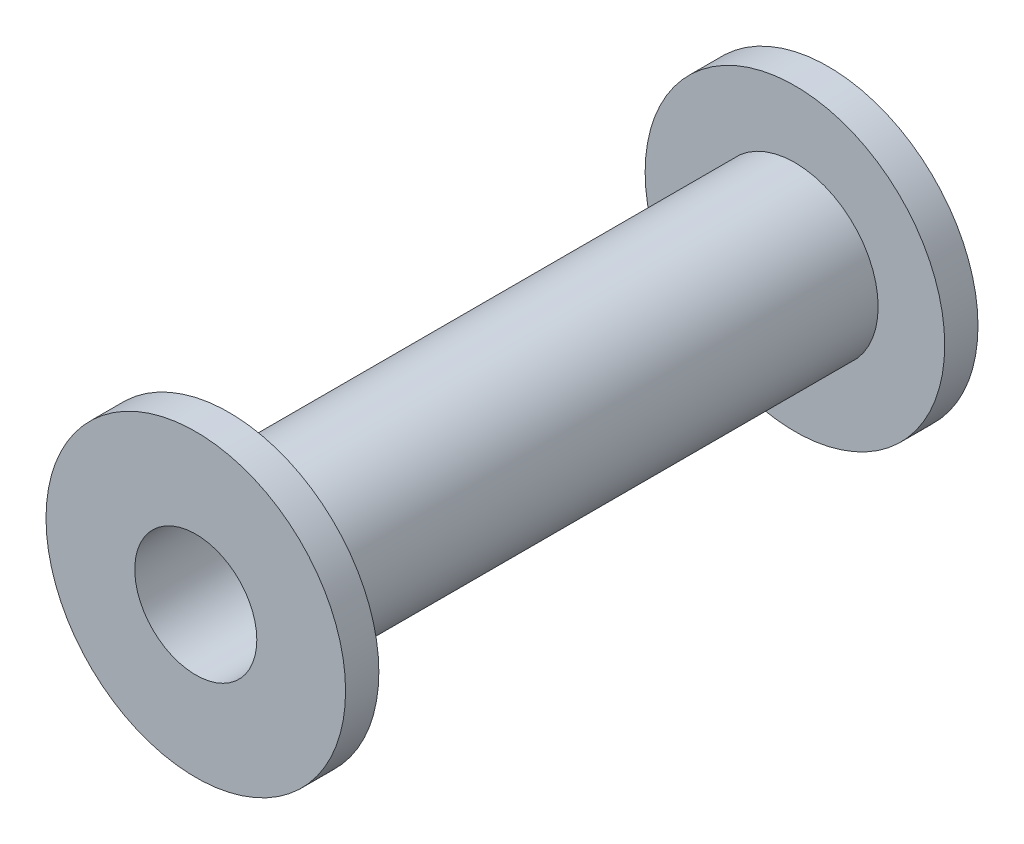
SolidWorks part; units mm, degrees
other "Marcação1"
sketch "Esboço7" plane through (13.5, -13.5, 0) normal (0.9554, -0.1863, -0.2291) x (-0.2848, -0.3761, -0.8818)
material "Filme de alta densidade PE"
ref_plane "Plano frontal" through (0, 0, 0) normal (0, 0, 1) x (1, 0, 0)
ref_plane "Plano superior" through (0, 0, 0) normal (0, 1, 0) x (1, 0, 0)
ref_plane "Plano direito" through (0, 0, 0) normal (1, 0, 0) x (0, 0, -1)
sketch "Esboço1" plane through (0, 0, 0) normal (0, 0, 1) x (1, 0, 0)
  circle A0 centre (0, 0) radius 5.5
  circle A1 centre (0, 0) radius 13.5
  dimension "D1" = 11
  dimension "D2" = 27
extrude "Ressalto-extrusão1" add sketch "Esboço1" along normal blind 3
sketch "Esboço2" plane through (0, 0, 3) normal (0, 0, 1) x (1, 0, 0)
  circle A0 centre (0, 0) radius 7.5
  circle A1 centre (0, 0) radius 5.5
  circle A2 centre (0, 0) radius 5.5 construction
  dimension "D1" = 15
extrude "Ressalto-extrusão2" add sketch "Esboço2" along normal blind 51
sketch "Esboço3" plane through (0, 0, 54) normal (0, 0, 1) x (1, 0, 0)
  circle A0 centre (0, 0) radius 13.5
  circle A1 centre (0, 0) radius 5.5
  dimension "D1" = 11
  dimension "D2" = 27
extrude "Ressalto-extrusão3" add sketch "Esboço3" along normal blind 3
sketch "Esboço6" plane through (0, 0, 0) normal (0, 0, -1) x (-1, 0, 0)
  line L0 (0, 0) -> (0, 9) construction
  dimension "D1" = 9
